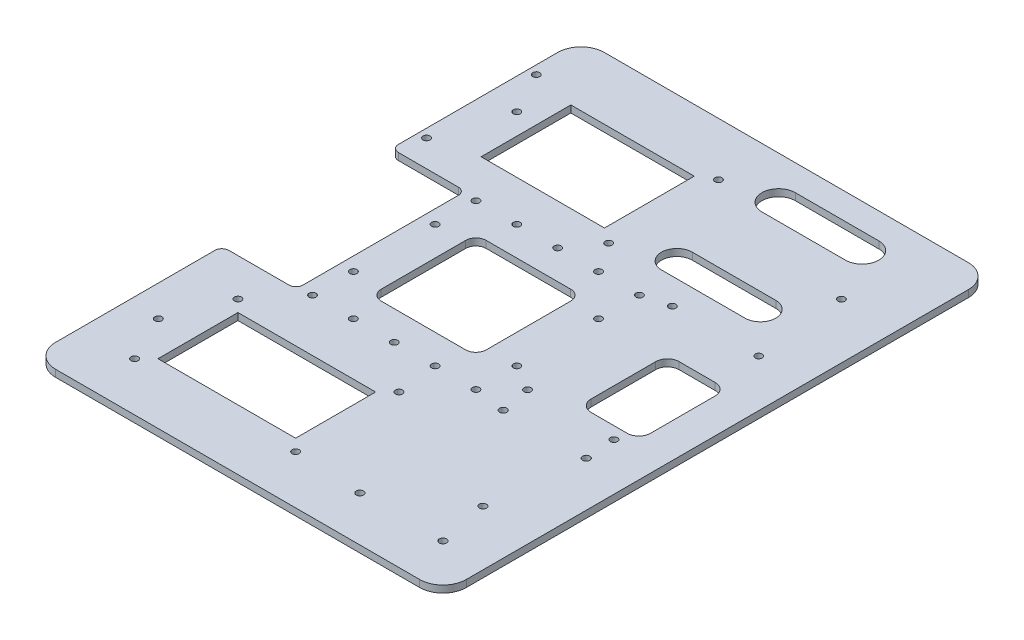
SolidWorks part; units mm, degrees
ref_plane "前视基准面" through (0, 0, 0) normal (0, 0, 1) x (1, 0, 0)
ref_plane "上视基准面" through (0, 0, 0) normal (0, 1, 0) x (1, 0, 0)
ref_plane "右视基准面" through (0, 0, 0) normal (1, 0, 0) x (0, 0, -1)
other "Configuration Table"
sketch "草图2" plane through (0, 0, 0) normal (0, 1, 0) x (1, 0, 0)
  line L0 (0, 0) -> (34826.5103, 0) construction
  line L1 (0, 0) -> (0, -34826.5103) construction
  line L2 (-72.5, -36.2939) -> (-72.5, -107.5)
  line L4 (-72.5, 107.5) -> (-72.5, 36.2939)
  line L7 (-62.5, 117.5) -> (93.3866, 117.5)
  line L8 (-62.5, -117.5) -> (93.3866, -117.5)
  line L15 (-35, 35) -> (35, 35) construction
  line L16 (-35, 35) -> (-35, -35) construction
  line L17 (-35, -35) -> (35, -35) construction
  line L18 (35, 35) -> (35, -35) construction
  line L19 (-35, 35) -> (35, -35) construction
  line L20 (-35, -35) -> (35, 35) construction
  line L21 (-18.1, 22.5) -> (18.1, 22.5)
  line L22 (-22.5, 18.1) -> (-22.5, -18.1)
  line L23 (-18.1, -22.5) -> (18.1, -22.5)
  line L24 (22.5, 18.1) -> (22.5, -18.1)
  line L25 (-22.5, 22.5) -> (22.5, -22.5) construction
  line L26 (-22.5, -22.5) -> (22.5, 22.5) construction
  line L30 (103.3866, 107.5) -> (103.3866, -107.5)
  line L32 (-49.5097, -52.4041) -> (-49.5097, -96.6641) construction
  line L33 (-72.5, -36.2939) -> (-40.7785, -36.2939)
  line L35 (-72.5, 36.2939) -> (-40.7785, 36.2939)
  line L36 (-40.7785, -36.2939) -> (-40.7785, 36.2939)
  line L37 (-49.5097, -96.6641) -> (19.4403, -96.6641) construction
  line L38 (19.4403, -52.4041) -> (19.4403, -96.6641) construction
  line L39 (-49.5097, -52.4041) -> (19.4403, -52.4041) construction
  line L40 (-44.5097, -57.4041) -> (-44.5097, -91.6641)
  line L41 (88.614, 18.8414) -> (63.156, 18.8414)
  line L42 (88.614, 18.8414) -> (88.614, -18.8414)
  line L43 (88.614, -18.8414) -> (63.156, -18.8414)
  line L44 (63.156, 18.8414) -> (63.156, -18.8414)
  line L45 (-44.5097, -91.6641) -> (14.4403, -91.6641)
  line L46 (14.4403, -57.4041) -> (14.4403, -91.6641)
  line L47 (-44.5097, -57.4041) -> (14.4403, -57.4041)
  line L49 (-50.2176, 90.862) -> (2.6188, 90.862)
  line L50 (-50.2176, 90.862) -> (-50.2176, 52.4282)
  line L51 (-50.2176, 52.4282) -> (2.6188, 52.4282)
  line L52 (2.6188, 90.862) -> (2.6188, 52.4282)
  circle A4 centre (-35, 35) radius 1.5
  circle A5 centre (35, 35) radius 1.5
  circle A6 centre (35, -35) radius 1.5
  circle A7 centre (-35, -35) radius 1.5
  arc A8 (-22.5, -18.1) -> (-18.1, -22.5) centre (-18.1, -18.1) ccw
  arc A9 (18.1, -22.5) -> (22.5, -18.1) centre (18.1, -18.1) ccw
  arc A10 (18.1, 22.5) -> (22.5, 18.1) centre (18.1, 18.1) cw
  arc A11 (-18.1, 22.5) -> (-22.5, 18.1) centre (-18.1, 18.1) ccw
  circle A12 centre (-17.5, 35) radius 1.5
  circle A13 centre (17.5, 35) radius 1.5
  circle A14 centre (-17.5, -35) radius 1.5
  circle A15 centre (17.5, -35) radius 1.5
  circle A16 centre (-35, 17.5) radius 1.5
  circle A17 centre (-35, -17.5) radius 1.5
  circle A18 centre (35, -17.5) radius 1.5
  circle A19 centre (35, 17.5) radius 1.5
  circle A20 centre (0, 35) radius 1.5
  circle A21 centre (0, -35) radius 1.5
  arc A22 (-62.5, 117.5) -> (-72.5, 107.5) centre (-62.5, 107.5) ccw
  arc A23 (-72.5, -107.5) -> (-62.5, -117.5) centre (-62.5, -107.5) ccw
  arc A24 (103.3866, -107.5) -> (93.3866, -117.5) centre (93.3866, -107.5) cw
  arc A25 (93.3866, 117.5) -> (103.3866, 107.5) centre (93.3866, 107.5) cw
  circle A34 centre (-49.5097, -52.4041) radius 1.5
  circle A35 centre (-49.5097, -96.6641) radius 1.5
  circle A36 centre (19.4403, -52.4041) radius 1.5
  circle A37 centre (19.4403, -96.6641) radius 1.5
  circle A38 centre (-59.25, -76.75) radius 1.5
  circle A39 centre (79.75, -76.75) radius 1.5
  circle A40 centre (79.75, 76.75) radius 1.5
  circle A41 centre (-59.25, 76.75) radius 1.5
  circle A42 centre (-68.8711, 94.7111) radius 1.5
  circle A43 centre (-68.8711, 47.7111) radius 1.5
  circle A44 centre (9.1289, 47.7111) radius 1.5
  circle A45 centre (9.1289, 94.7111) radius 1.5
  circle A46 centre (48.5314, -36.8541) radius 1.55
  circle A47 centre (84.0914, -36.8541) radius 1.55
  circle A48 centre (48.5314, -98.2341) radius 1.55
  circle A49 centre (84.0914, -98.2341) radius 1.55
  circle A50 centre (46.1314, 37.9696) radius 1.5
  circle A51 centre (83.1314, 37.9696) radius 1.5
  circle A52 centre (46.1314, -24.0304) radius 1.5
  circle A53 centre (83.1314, -24.0304) radius 1.5
  point P5 (0, 0)
  point P10 (0, 0)
  point P11 (0, 0)
  point P19 (0, 0)
  point P40 (-72.5, 117.5)
  point P43 (-72.5, -117.5)
  dimension "D3" = 45
  dimension "D4" = 3
  dimension "D6" = 4.4
  dimension "D7" = 17.5
  dimension "D8" = 3
  dimension "D9" = 3
  dimension "D11" = 3
  dimension "D12" = 3
  dimension "D14" = 10
  dimension "D16" = 68.95
  dimension "D2" = 45
  dimension "D5" = 70
  dimension "D10" = 17.5
  dimension "D13" = 235
  dimension "D15" = 44.26
  dimension "D17" = 5
extrude "凸台-拉伸2" add sketch "草图2" along normal blind 3
fillet "圆角2" radius 3 4 edges at (-40.7785, 1.5, 36.2939) (-40.7785, 1.5, -36.2939) (-72.5, 1.5, 36.2939) (-72.5, 1.5, -36.2939)
fillet "圆角3" radius 5 4 edges at (88.614, 1.5, -18.8414) (63.156, 1.5, -18.8414) (63.156, 1.5, 18.8414) (88.614, 1.5, 18.8414)
sketch "草图3" plane through (0, 3, 0) normal (0, 1, 0) x (1, 0, 0)
  line L0 (30.3803, 99.2435) -> (66.1384, 99.2435) construction
  line L1 (30.3803, 106.3927) -> (66.1384, 106.3927)
  line L2 (30.3803, 92.0943) -> (66.1384, 92.0943)
  line L3 (30.3803, 55.6763) -> (66.1384, 55.6763) construction
  line L4 (30.3803, 62.2745) -> (66.1384, 62.2745)
  line L5 (30.3803, 49.0781) -> (66.1384, 49.0781)
  arc A0 (30.3803, 106.3927) -> (30.3803, 92.0943) centre (30.3803, 99.2435) ccw
  arc A1 (66.1384, 92.0943) -> (66.1384, 106.3927) centre (66.1384, 99.2435) ccw
  arc A2 (30.3803, 62.2745) -> (30.3803, 49.0781) centre (30.3803, 55.6763) ccw
  arc A3 (66.1384, 49.0781) -> (66.1384, 62.2745) centre (66.1384, 55.6763) ccw
  point P2 (48.2593, 99.2435)
  point P7 (48.2593, 55.6763)
  point P14 (48.2593, 99.2435)
extrude "切除-拉伸1" cut sketch "草图3" against normal through all
